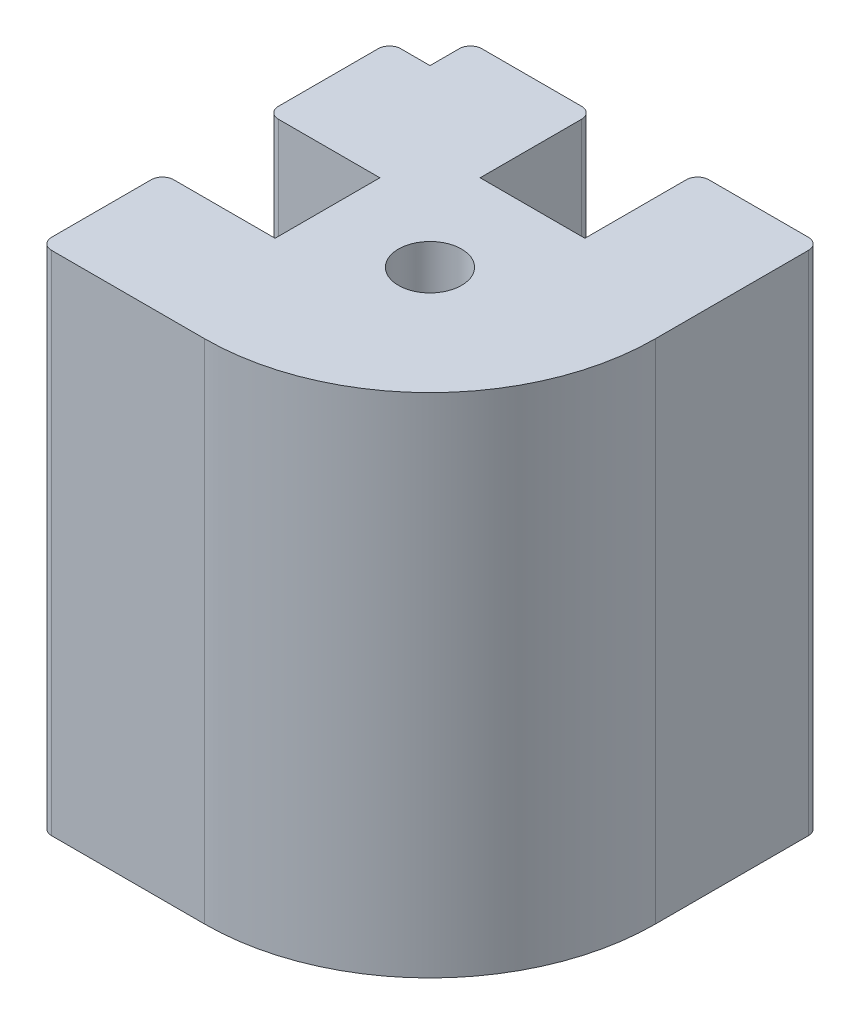
SolidWorks part; units mm, degrees
ref_plane "Front Plane" through (0, 0, 0) normal (0, 0, 1) x (1, 0, 0)
ref_plane "Top Plane" through (0, 0, 0) normal (0, 1, 0) x (1, 0, 0)
ref_plane "Right Plane" through (0, 0, 0) normal (1, 0, 0) x (0, 0, -1)
sketch "Sketch1" plane through (0, 0, 0) normal (0, 1, 0) x (1, 0, 0)
  line L0 (-19.0992, -15.5) -> (-19.0992, -4.65)
  line L1 (-19.0992, -4.65) -> (-9.0992, -4.65)
  line L2 (-9.0992, -4.65) -> (-9.0992, 4.65)
  line L3 (-9.0992, 4.65) -> (-19.0992, 4.65)
  line L4 (-19.0992, 4.65) -> (-19.0992, 15.5)
  line L5 (-19.0992, 15.5) -> (-15.5, 15.5)
  line L6 (-15.5, 15.5) -> (-15.5, 19.0992)
  line L7 (-15.5, 19.0992) -> (-4.65, 19.0992)
  line L8 (-4.65, 19.0992) -> (-4.65, 9.0992)
  line L9 (-4.65, 9.0992) -> (4.65, 9.0992)
  line L10 (4.65, 9.0992) -> (4.65, 19.0992)
  line L11 (4.65, 19.0992) -> (15.5, 19.0992)
  line L12 (15.5, 19.0992) -> (15.5, -15.5)
  line L13 (15.5, -15.5) -> (-19.0992, -15.5)
  circle A0 centre (0, 0) radius 2.8
  point P5 (-9.0992, 0)
  point P15 (0, 9.0992)
  dimension "D4" = 5.6
  dimension "D1" = 9.3
  dimension "D2" = 10
  dimension "D3" = 31
extrude "Boss-Extrude1" add sketch "Sketch1" along normal blind 45
fillet "Fillet1" radius 1 8 edges at (15.5, 22.5, -19.0992) (4.65, 22.5, -19.0992) (-4.65, 22.5, -19.0992) (-15.5, 22.5, -19.0992) (-19.0992, 22.5, -15.5) (-19.0992, 22.5, 4.65) (-19.0992, 22.5, -4.65) (-19.0992, 22.5, 15.5)
fillet "Fillet2" radius 20 1 edges at (15.5, 22.5, 15.5)
